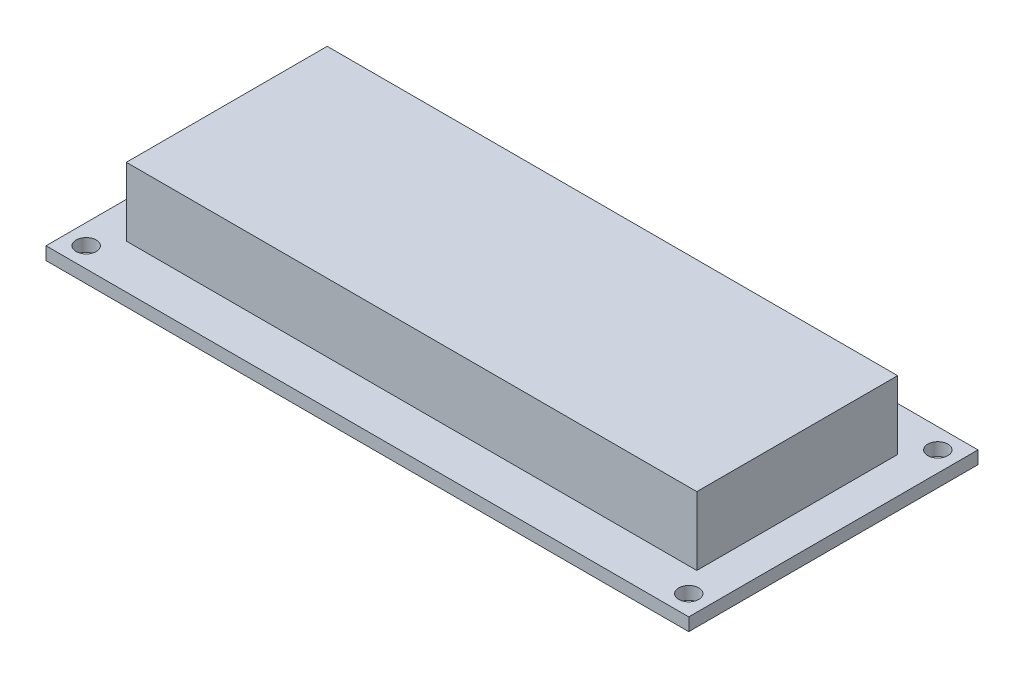
SolidWorks part; units mm, degrees
ref_plane "Front Plane" through (0, 0, 0) normal (0, 0, 1) x (1, 0, 0)
ref_plane "Top Plane" through (0, 0, 0) normal (0, 1, 0) x (1, 0, 0)
ref_plane "Right Plane" through (0, 0, 0) normal (1, 0, 0) x (0, 0, -1)
sketch "Sketch1" plane through (0, 0, 0) normal (0, 1, 0) x (1, 0, 0)
  line L1 (-40, 18) -> (40, 18)
  line L2 (-40, 18) -> (-40, -18)
  line L3 (-40, -18) -> (40, -18)
  line L4 (40, 18) -> (40, -18)
  line L5 (-40, 18) -> (40, -18) construction
  line L6 (-40, -18) -> (40, 18) construction
  point P0 (0, 0)
  dimension "D1" = 36
  dimension "D2" = 80
extrude "Boss-Extrude1" add sketch "Sketch1" along normal blind 1.6
sketch "Sketch2" plane through (0, 1.6, 0) normal (0, 1, 0) x (1, 0, 0)
  line L0 (-37.5, 15.5) -> (37.5, 15.5) construction
  line L1 (37.5, 15.5) -> (37.5, -15.5) construction
  line L2 (37.5, -15.5) -> (-37.5, -15.5) construction
  line L3 (-37.5, -15.5) -> (-37.5, 15.5) construction
  line L4 (-37.5, 15.5) -> (37.5, -15.5) construction
  circle A0 centre (-37.5, 15.5) radius 1.25
  circle A1 centre (37.5, 15.5) radius 1.25
  circle A2 centre (37.5, -15.5) radius 1.25
  circle A3 centre (-37.5, -15.5) radius 1.25
  dimension "D1" = 2.5
  dimension "D2" = 75
  dimension "D3" = 31
extrude "Cut-Extrude1" cut sketch "Sketch2" against normal blind 1.6
sketch "Sketch3" plane through (0, 1.6, 0) normal (0, 1, 0) x (1, 0, 0)
  line L1 (35.5, 12.5) -> (-35.5, 12.5)
  line L2 (35.5, 12.5) -> (35.5, -12.5)
  line L3 (35.5, -12.5) -> (-35.5, -12.5)
  line L4 (-35.5, 12.5) -> (-35.5, -12.5)
  line L5 (35.5, 12.5) -> (-35.5, -12.5) construction
  line L6 (35.5, -12.5) -> (-35.5, 12.5) construction
  point P0 (0, 0)
  dimension "D1" = 71
  dimension "D2" = 25
extrude "Boss-Extrude2" add sketch "Sketch3" along normal blind 8.5
sketch "Sketch4" plane through (0, 1.6, 0) normal (0, 1, 0) x (1, 0, 0)
  line L0 (-33, 16) -> (-33, 18)
  line L1 (40, 18) -> (-40, 18) construction
  line L2 (-33, 18) -> (-31, 18)
  line L3 (-31, 18) -> (-31, 16)
  line L4 (-40, 18) -> (-40, -18) construction
  arc A0 (-33, 16) -> (-31, 16) centre (-32, 16) ccw
  circle A1 centre (-32, 16) radius 0.2611
  dimension "D1" = 2
  dimension "D2" = 2
  dimension "D3" = 8
extrude "Boss-Extrude3" add sketch "Sketch4" along normal blind 0.1
pattern_linear "LPattern1" count 16 spacing 2.54 along (1, 0, 0) of "Boss-Extrude3"
